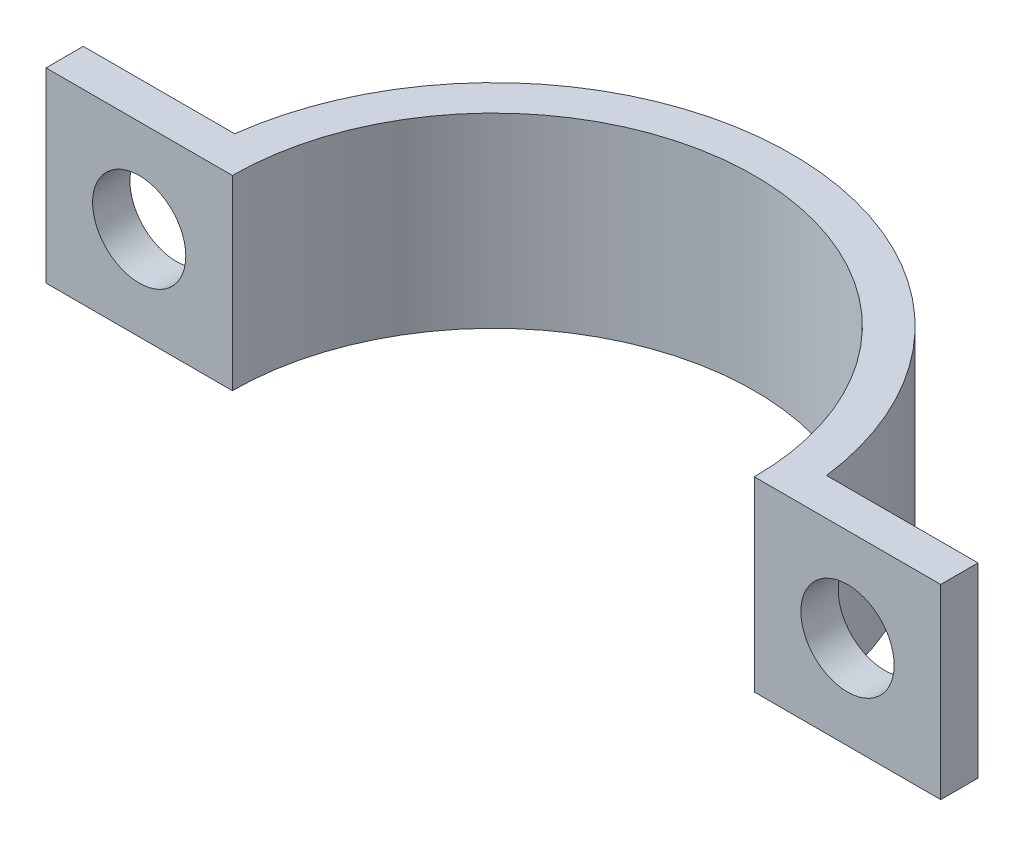
SolidWorks part; units mm, degrees
ref_plane "Спереди" through (0, 0, 0) normal (0, 0, 1) x (1, 0, 0)
ref_plane "Сверху" through (0, 0, 0) normal (0, 1, 0) x (1, 0, 0)
ref_plane "Справа" through (0, 0, 0) normal (1, 0, 0) x (0, 0, -1)
sketch "Эскиз1" plane through (0, 0, 0) normal (0, 1, 0) x (1, 0, 0)
  line L0 (-14, 0) -> (-24, 0)
  line L1 (14, 0) -> (24, 0)
  line L2 (-15.8745, 2) -> (-24, 2)
  line L3 (15.8745, 2) -> (24, 2)
  line L4 (-24, 2) -> (-24, 0)
  line L5 (24, 2) -> (24, 0)
  arc A0 (-14, 0) -> (14, 0) centre (0, 0) cw
  arc A1 (-15.8745, 2) -> (15.8745, 2) centre (0, 0) cw
  dimension "D1" = 10
  dimension "D4" = 14
  dimension "D2" = 10
  dimension "D3" = 2
extrude "Бобышка-Вытянуть1" add sketch "Эскиз1" along normal blind 10
sketch "Эскиз2" plane through (0, 0, 0) normal (0, 0, 1) x (1, 0, 0)
  line L0 (-19, 10) -> (-19, 0) construction
  line L1 (-24, 10) -> (-14, 10) construction
  line L2 (-24, 0) -> (-14, 0) construction
  line L4 (-24, 10) -> (-24, 0) construction
  line L5 (-24, 5) -> (-14, 5) construction
  line L6 (-14, 10) -> (-14, 0) construction
  circle A0 centre (-19, 5) radius 2.5
extrude "Вырез-Вытянуть1" cut sketch "Эскиз2" against normal through all
mirror "Зеркальное отражение1" about plane through (0, 0, 0) normal (1, 0, 0) of "Вырез-Вытянуть1"
